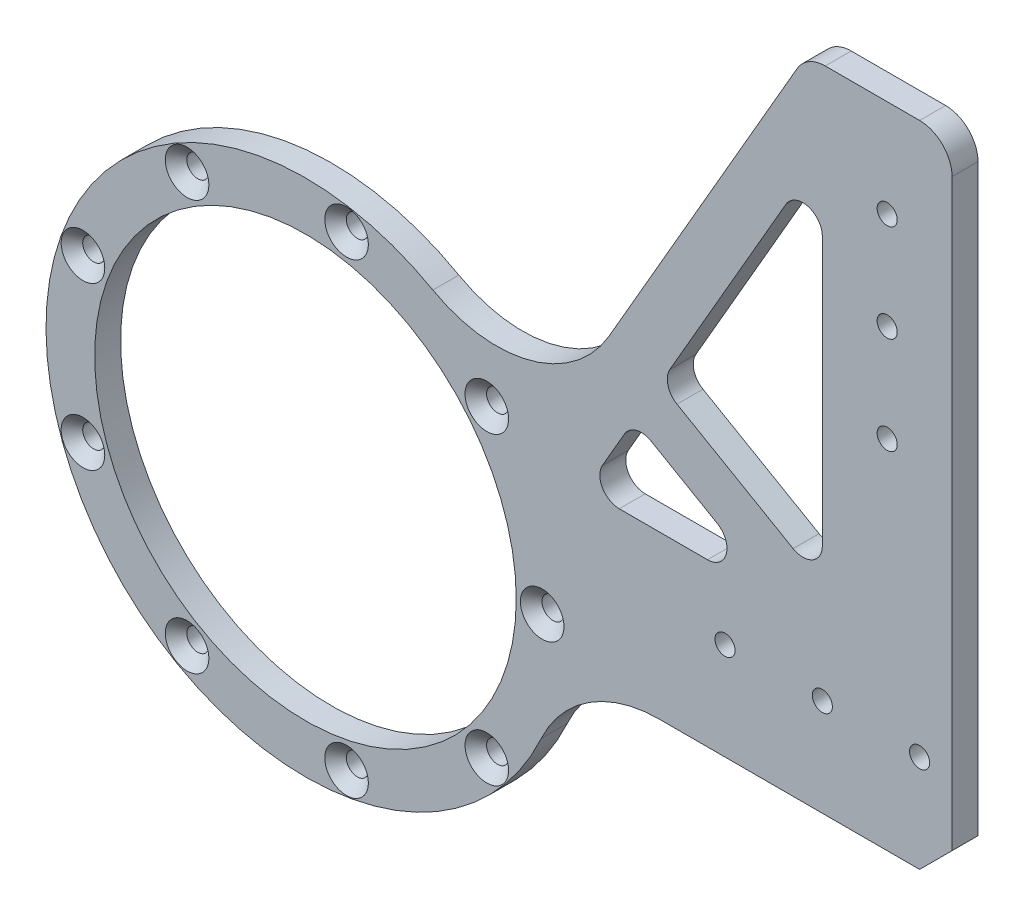
SolidWorks part; units mm, degrees
material "Thornel Mat VMA"
ref_plane "前视基准面" through (0, 0, 0) normal (0, 0, 1) x (1, 0, 0)
ref_plane "上视基准面" through (0, 0, 0) normal (0, 1, 0) x (1, 0, 0)
ref_plane "右视基准面" through (0, 0, 0) normal (1, 0, 0) x (0, 0, -1)
other "Configuration Table"
sketch "草图1" plane through (0, 0, 0) normal (0, 0, 1) x (1, 0, 0)
  circle A0 centre (0, 0) radius 40
  circle A10 centre (0, 0) radius 32.5
  dimension "D1" = 80
  dimension "D6" = 65
extrude "凸台-拉伸1" add sketch "草图1" along normal blind 4
sketch "草图2" plane through (0, 0, 4) normal (0, 0, 1) x (1, 0, 0)
  line L0 (0, 0) -> (40, 0) construction
  line L1 (0, 0) -> (36.5, 0) construction
  circle A0 centre (0, 0) radius 40 construction
  point P6 (36.5, 0)
  point P7 (27.9606, -23.4617)
  point P10 (6.3382, -35.9455)
  point P11 (-18.25, -31.6099)
  point P12 (-34.2988, -12.4837)
  point P13 (-34.2988, 12.4837)
  point P14 (-18.25, 31.6099)
  point P15 (6.3382, 35.9455)
  point P16 (27.9606, 23.4617)
  dimension "D3" = 36.5
  dimension "D2" = 9
hole_wizard "M3 六角凹锥坑螺钉的锥形沉头孔1" positions "草图2" profile "草图3" countersink size "M3" standard "ISO" end condition through all
sketch "草图3" plane through (27.9606, 23.4617, 4) normal (1, 0, 0) x (0, -1, 0)
  line L0 (0, 0) -> (0, 4)
  line L1 (0, 4) -> (1.7, 4)
  line L2 (1.7, 4) -> (1.7, 1.66)
  line L3 (1.7, 1.66) -> (3.36, 0)
  line L5 (3.36, 0) -> (0, 0)
  line L6 (-1.7, 1.66) -> (-3.36, 0) construction
  line L11 (0, -6.35) -> (0, 107.95) construction
  dimension "通孔孔直径" = 3.4
  dimension "通孔孔深度" = 4
  dimension "近端锥形沉头孔直径" = 6.72
  dimension "近端锥形沉头孔角度" = 90
sketch "草图4" plane through (0, 0, 4) normal (0, 0, 1) x (1, 0, 0)
  line L0 (0, 0) -> (40, 0) construction
  line L11 (39.6863, -5) -> (99.6863, -5)
  line L23 (77.2499, 95) -> (99.6863, 95)
  line L26 (99.6863, 95) -> (99.6863, -5)
  line L27 (77.2499, 95) -> (34.2914, 20.5937)
  line L28 (79.6863, 83.2199) -> (43.1863, 20) construction
  line L29 (43.1863, 20) -> (79.6863, 20) construction
  line L30 (79.6863, 20) -> (79.6863, 83.2199) construction
  line L32 (54.6863, 39.9186) -> (79.6863, 25.4848)
  line L33 (50.6863, 32.9904) -> (73.1863, 20)
  line L34 (79.6863, 83.2199) -> (54.6863, 39.9186)
  line L35 (79.6863, 83.2199) -> (79.6863, 25.4848)
  line L36 (50.6863, 32.9904) -> (43.1863, 20)
  line L37 (43.1863, 20) -> (73.1863, 20)
  line L38 (89.6863, 95) -> (89.6863, -5) construction
  circle A0 centre (0, 0) radius 40 construction
  circle A5 centre (79.6863, 10) radius 1.55
  circle A13 centre (94.6863, 10) radius 1.55
  circle A29 centre (64.6863, 10) radius 1.55
  circle A34 centre (89.6863, 80) radius 1.55
  arc A42 (34.2914, 20.5937) -> (39.6863, -5) centre (0, 0) cw
  circle A43 centre (89.6863, 65) radius 1.55
  circle A44 centre (89.6863, 50) radius 1.55
  point P29 (71.3476, 20)
  point P30 (0, 0)
  dimension "D1" = 5
  dimension "D2" = 20
  dimension "D8" = 3.1
  dimension "D9" = 3.1
  dimension "D10" = 15
  dimension "D15" = 15
  dimension "D16" = 15
  dimension "D18" = 10
  dimension "D19" = 3.1
  dimension "D25" = 15
  dimension "D26" = 50
  dimension "D6" = 60
  dimension "D11" = 15
  dimension "D3" = 60
  dimension "D14" = 3.1
  dimension "D20" = 3.1
  dimension "D21" = 3.1
  dimension "D4" = 100
  dimension "D5" = 25
  dimension "D7" = 8
  dimension "D12" = 15
  dimension "D13" = 5
  dimension "D17" = 8
  dimension "D22" = 15
  dimension "D23" = 15
  dimension "D24" = 15
extrude "凸台-拉伸2" add sketch "草图4" against normal up to surface (4 mm away) up to face at (38.2, 0, 0)
fillet "圆角1" [suppressed] radius 10
fillet "圆角2" radius 20 2 edges at (39.6863, -5, 2) (34.2914, 20.5937, 2)
fillet "圆角3" [suppressed] radius 20
chamfer "倒角1" distance 5 angle 45 1 edges at (99.6863, -5, 2)
fillet "圆角4" radius 3 6 edges at (43.1863, 20, 2) (50.6863, 32.9904, 2) (73.1863, 20, 2) (54.6863, 39.9186, 2) (79.6863, 83.2199, 2) (79.6863, 25.4848, 2)
fillet "圆角5" radius 5 2 edges at (77.2499, 95, 2) (99.6863, 95, 2)
